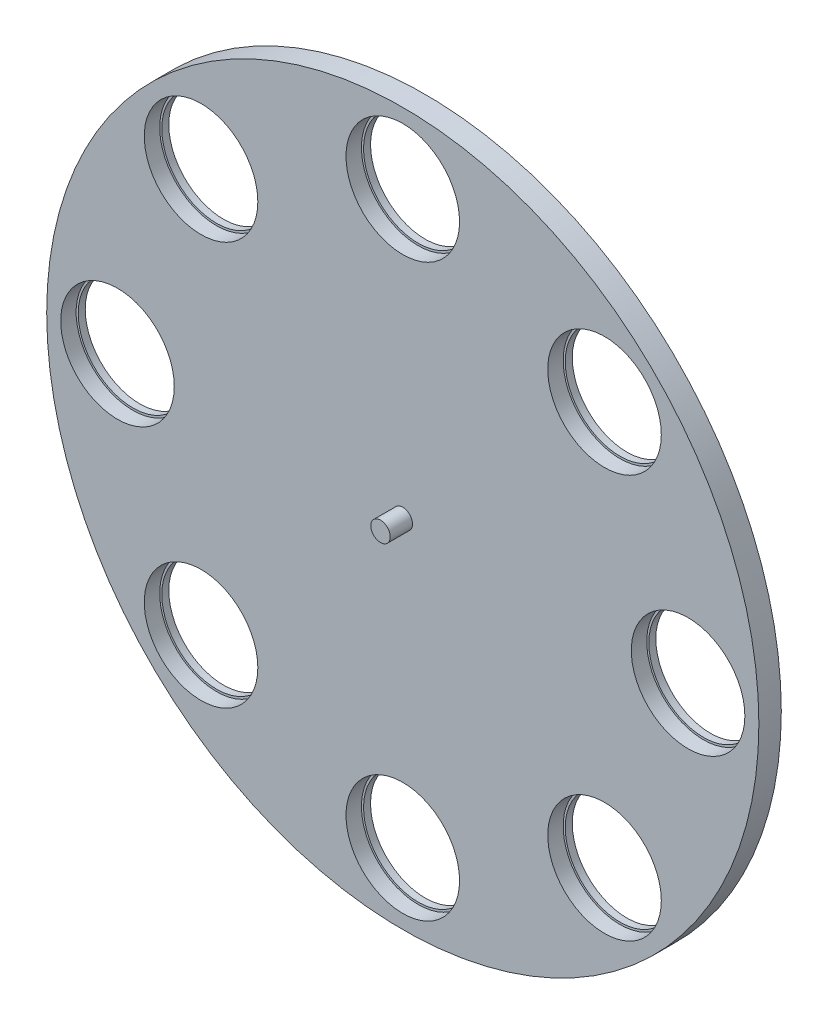
SolidWorks part; units mm, degrees
material "VeroWhite Plus"
ref_plane "Front Plane" through (0, 0, 0) normal (0, 0, 1) x (1, 0, 0)
ref_plane "Top Plane" through (0, 0, 0) normal (0, 1, 0) x (1, 0, 0)
ref_plane "Right Plane" through (0, 0, 0) normal (1, 0, 0) x (0, 0, -1)
sketch "Sketch1" plane through (0, 0, 0) normal (0, 0, 1) x (1, 0, 0)
  line L0 (0, 0) -> (0, 43.1092) construction
  circle A0 centre (0, 0) radius 25.4
  circle A1 centre (0, 0) radius 0.7937 construction
  circle A2 centre (0, 0) radius 0.6937 construction
  circle A3 centre (0, 20.35) radius 4.05
  circle A4 centre (14.3896, 14.3896) radius 4.05
  circle A5 centre (20.35, 0) radius 4.05
  circle A6 centre (14.3896, -14.3896) radius 4.05
  circle A7 centre (0, -20.35) radius 4.05
  circle A8 centre (-14.3896, -14.3896) radius 4.05
  circle A9 centre (-20.35, 0) radius 4.05
  circle A10 centre (-14.3896, 14.3896) radius 4.05
  point P10 (0, 24.4)
  point P11 (0, 25.4)
  dimension "D2" = 8.1
  dimension "D5" = 50.8
  dimension "D3" = 1
  dimension "D1" = 0.1
  dimension "D4" = 8
extrude "Boss-Extrude1" add sketch "Sketch1" along normal blind 1.1
sketch "Sketch2" plane through (0, 0, 1.1) normal (0, 0, 1) x (1, 0, 0)
  circle A0 centre (0, 0) radius 0.6937 construction
  circle A1 centre (0, 0) radius 0.6937
extrude "Boss-Extrude2" add sketch "Sketch2" along normal blind 1.5875
sketch "Sketch3" plane through (0, 0, 0) normal (0, 0, -1) x (-1, 0, 0)
  circle A0 centre (14.3896, 14.3896) radius 4.05 construction
  circle A1 centre (0, 0) radius 25.4
  circle A2 centre (0, 0) radius 25.4
  circle A3 centre (20.35, 0) radius 4.05 construction
  circle A4 centre (14.3896, -14.3896) radius 4.05 construction
  circle A5 centre (0, -20.35) radius 4.05 construction
  circle A6 centre (-14.3896, -14.3896) radius 4.05 construction
  circle A7 centre (-20.35, 0) radius 4.05 construction
  circle A8 centre (-14.3896, 14.3896) radius 4.05 construction
  circle A9 centre (0, 20.35) radius 4.05 construction
  circle A10 centre (14.3896, 14.3896) radius 4.05 construction
  circle A11 centre (20.35, 0) radius 4.05 construction
  circle A12 centre (14.3896, -14.3896) radius 4.05 construction
  circle A13 centre (0, -20.35) radius 4.05 construction
  circle A14 centre (-14.3896, -14.3896) radius 4.05 construction
  circle A15 centre (-20.35, 0) radius 4.05 construction
  circle A16 centre (-14.3896, 14.3896) radius 4.05 construction
  circle A17 centre (0, 20.35) radius 4.05 construction
  circle A18 centre (0, 20.35) radius 3.9
  circle A26 centre (14.3896, 14.3896) radius 3.9
  circle A27 centre (20.35, 0) radius 3.9
  circle A28 centre (14.3896, -14.3896) radius 3.9
  circle A29 centre (0, -20.35) radius 3.9
  circle A30 centre (-14.3896, -14.3896) radius 3.9
  circle A31 centre (-20.35, 0) radius 3.9
  circle A32 centre (-14.3896, 14.3896) radius 3.9
  dimension "D2" = 7.8
  dimension "D1" = 0
  dimension "D3" = 8
extrude "Boss-Extrude3" add sketch "Sketch3" along normal blind 0.5
